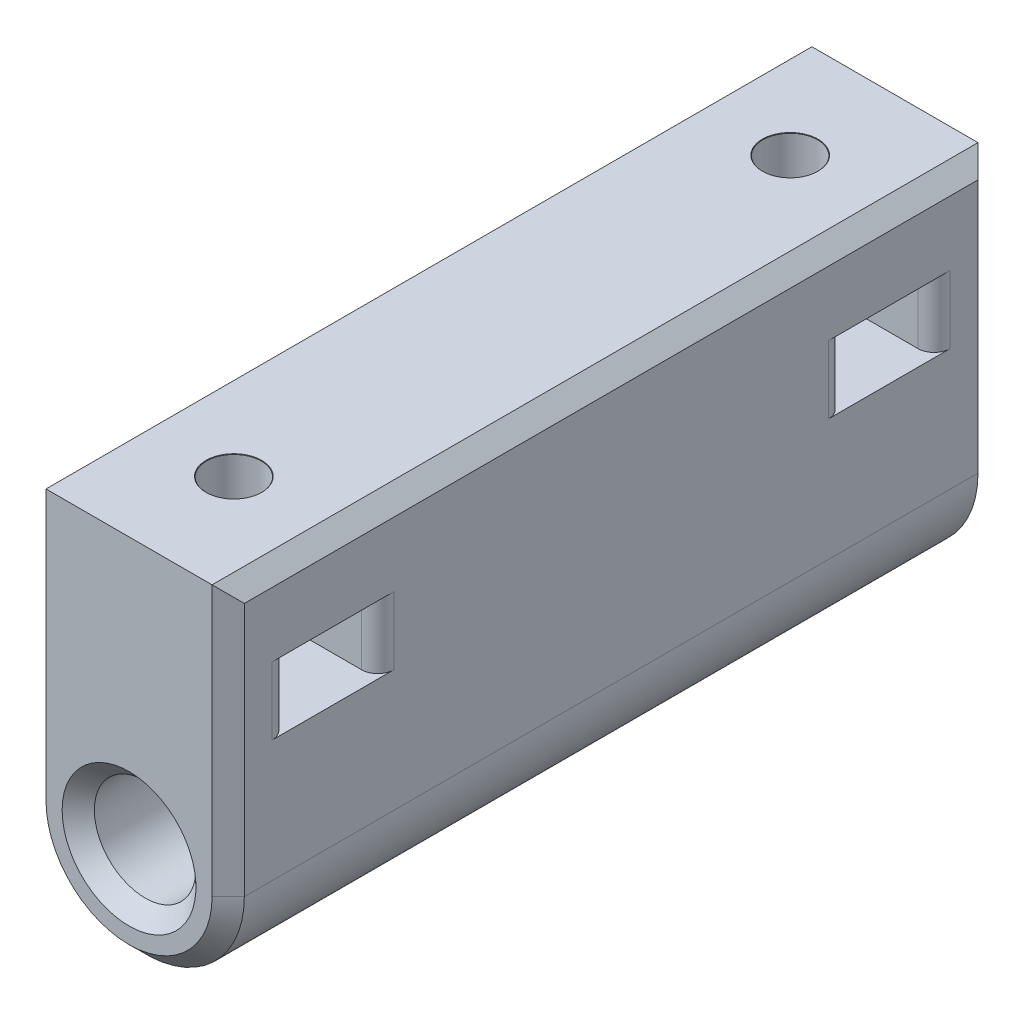
SolidWorks part; units mm, degrees
material "Hollow 3D Print"
ref_plane "Front Plane" through (0, 0, 0) normal (0, 0, 1) x (1, 0, 0)
ref_plane "Top Plane" through (0, 0, 0) normal (0, 1, 0) x (1, 0, 0)
ref_plane "Right Plane" through (0, 0, 0) normal (1, 0, 0) x (0, 0, -1)
sketch "Sketch1" plane through (0, 0, 0) normal (0, 0, 1) x (1, 0, 0)
  line L0 (0, 0) -> (0, 16.75) construction
  line L1 (6.15, 0) -> (6.15, 16.75)
  line L2 (-6.15, 0) -> (-6.15, 16.75)
  line L3 (-6.15, 16.75) -> (6.15, 16.75)
  circle A0 centre (0, 0) radius 3.15
  arc A1 (6.15, 0) -> (-6.15, 0) centre (0, 0) cw
  dimension "D2" = 3
  dimension "D3" = 6.3
  dimension "D1" = 16.75
extrude "Boss-Extrude1" add sketch "Sketch1" along normal blind 47.5
sketch "Sketch3" plane through (6.15, 0, 0) normal (1, 0, 0) x (0, 0, -1)
  line L1 (-47.5, 16.75) -> (0, 16.75) construction
  line L2 (-25.85, 6.15) -> (-21.65, 6.15)
  line L4 (-23.75, 6.15) -> (-23.75, 16.75) construction
  line L6 (-47.5, 0) -> (0, 0) construction
  line L7 (0, -6.15) -> (0, 0) construction
  line L8 (0, -6.15) -> (0, 0) construction
  line L9 (-23.75, 6.15) -> (-23.75, 0) construction
  point P8 (-23.75, 0)
ref_plane "Plane1" through (0, 11.75, 0) normal (0, 1, 0) x (1, 0, 0)
sketch "Sketch4" plane through (0, 11.75, 0) normal (0, 1, 0) x (1, 0, 0)
  line L0 (6.15, -47.5) -> (-6.15, -47.5) construction
  line L1 (-3.2043, -41) -> (-1.6021, -43.775)
  line L2 (-1.6021, -43.775) -> (1.6021, -43.775)
  line L3 (1.6021, -43.775) -> (3.2043, -41) construction
  line L4 (3.2043, -41) -> (1.6021, -38.225) construction
  line L5 (1.6021, -38.225) -> (-1.6021, -38.225)
  line L6 (-1.6021, -38.225) -> (-3.2043, -41)
  line L7 (6.15, -47.5) -> (-6.15, -47.5)
  line L8 (0, -47.5) -> (0, -41) construction
  line L9 (1.6021, -38.225) -> (6.15, -38.225)
  line L10 (6.15, -38.225) -> (6.15, -43.775)
  line L11 (6.15, -43.775) -> (1.6021, -43.775)
  circle A0 centre (0, -41) radius 2.775 construction
  dimension "D1" = 5.55
  dimension "D2" = 6.5
extrude "Cut-Extrude1" cut sketch "Sketch4" against normal blind 4.2 contours L11 L2 L1 L6 L5 L9 L10
ref_plane "Plane2" through (0, 0, 23.75) normal (0, 0, -1) x (-1, 0, 0)
sketch "Sketch6" plane through (0, 16.75, 0) normal (0, 1, 0) x (1, 0, 0)
  point P0 (0, -41)
hole_wizard "M3 Clearance Hole1" positions "Sketch6" profile "Sketch7" hole size "M3" standard "ANSI Metric"
sketch "Sketch7" plane through (0, 16.75, 41) normal (1, 0, 0) x (0, 0, 1)
  line L0 (0, 0) -> (0, 17.7705)
  line L1 (0, 17.7705) -> (1.7, 16.749)
  line L2 (1.7, 16.749) -> (1.7, 0.025)
  line L3 (1.7, 0.025) -> (1.725, 0)
  line L5 (1.725, 0) -> (0, 0)
  line L6 (-1.7, 0.025) -> (-1.725, 0) construction
  line L10 (0, 17.7705) -> (-1.7, 16.749) construction
  line L11 (0, -6.35) -> (0, 107.95) construction
  dimension "Hole Dia." = 3.4
  dimension "Hole Depth" = 16.749
  dimension "Near C'Sink Dia." = 3.45
  dimension "Near C'Sink Angle" = 90
  dimension "Drill Angle" = 118
mirror "Mirror1" about plane through (0, 0, 23.75) normal (0, 0, -1) of "M3 Clearance Hole1", "Cut-Extrude1"
fillet "Fillet1" radius 1 4 edges at (6.15, 9.65, 9.275) (6.15, 9.65, 3.725) (6.15, 9.65, 43.775) (6.15, 9.65, 38.225)
chamfer "Chamfer1" distance 1 angle 45 8 edges at (-6.15, 16.75, 23.75) (-6.15, 8.375, 0) (-6.15, 8.375, 47.5) (0, -6.15, 0) (0, -6.15, 47.5) (6.15, 8.375, 0) (6.15, 16.75, 23.75) (6.15, 8.375, 47.5)
chamfer "Chamfer2" distance 1 angle 45 2 edges at (3.15, 0, 0) (3.15, 0, 47.5)
